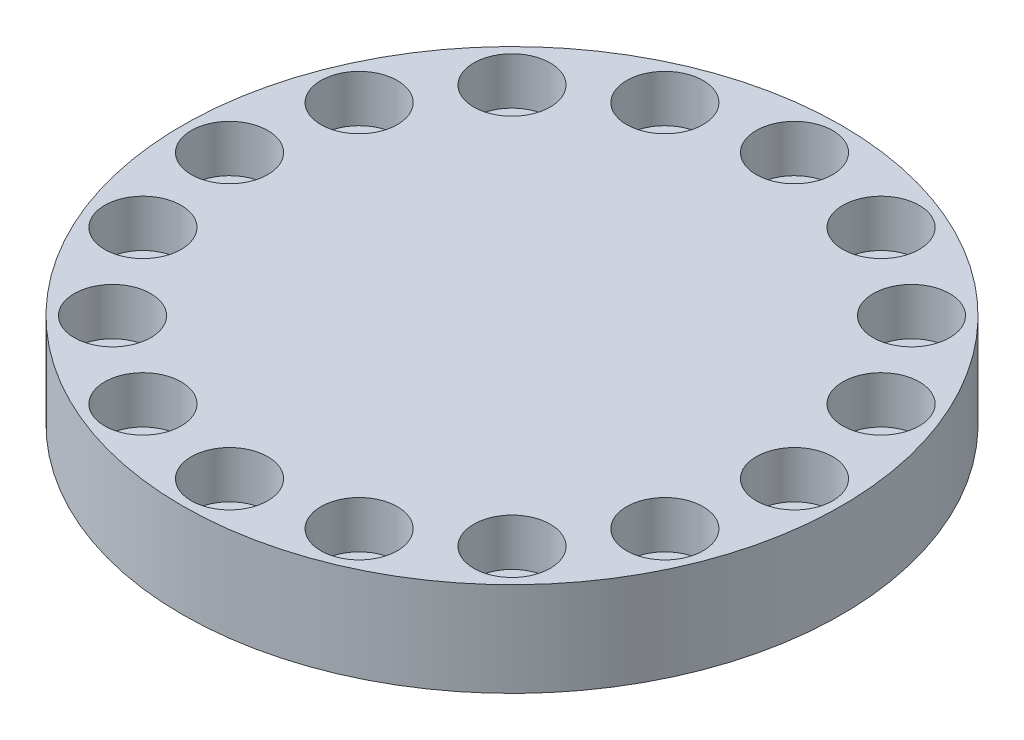
SolidWorks part; units mm, degrees
ref_plane "Front Plane" through (0, 0, 0) normal (0, 0, 1) x (1, 0, 0)
ref_plane "Top Plane" through (0, 0, 0) normal (0, 1, 0) x (1, 0, 0)
ref_plane "Right Plane" through (0, 0, 0) normal (1, 0, 0) x (0, 0, -1)
sketch "Sketch1" plane through (0, 0, 0) normal (0, 1, 0) x (1, 0, 0)
  circle A0 centre (0, 0) radius 88.9
  dimension "D1" = 177.8
extrude "Boss-Extrude1" add sketch "Sketch1" against normal blind 25.4
sketch "Sketch2" plane through (0, 0, 0) normal (0, 1, 0) x (1, 0, 0)
  line L0 (0, 76.2) -> (0, 0) construction
  circle A0 centre (0, 76.2) radius 6.731
  circle A1 centre (0, 0) radius 76.2 construction
  dimension "D1" = 13.462
  dimension "D2" = 152.4
hole_wizard "CBORE for 1/2 Socket Head Cap Screw1" positions "Sketch3" profile "Sketch4" counterbore size "1/2" standard "ANSI Inch" end condition through all
sketch "Sketch3" plane through (0, 0, 0) normal (0, 1, 0) x (1, 0, 0)
  point P0 (0, 76.2)
sketch "Sketch4" plane through (0, 0, -76.2) normal (1, 0, 0) x (0, 0, 1)
  line L0 (0, 0) -> (0, 25.4)
  line L1 (0, 25.4) -> (6.7462, 25.4)
  line L3 (6.7462, 25.4) -> (6.7462, 12.7)
  line L4 (6.7462, 12.7) -> (10.3187, 12.7)
  line L5 (10.3187, 12.7) -> (10.3187, 0)
  line L7 (10.3187, 0) -> (0, 0)
  line L11 (0, -6.35) -> (0, 107.95) construction
  dimension "Thru Hole Dia." = 13.4925
  dimension "Thru Hole Depth" = 25.4
  dimension "C'Bore Dia." = 20.6375
  dimension "C'Bore Depth" = 12.7
pattern_circular "CirPattern1" count 16 over 360 about axis through (0, 0, 0) along (0, 1, 0) of "CBORE for 1/2 Socket Head Cap Screw1"
